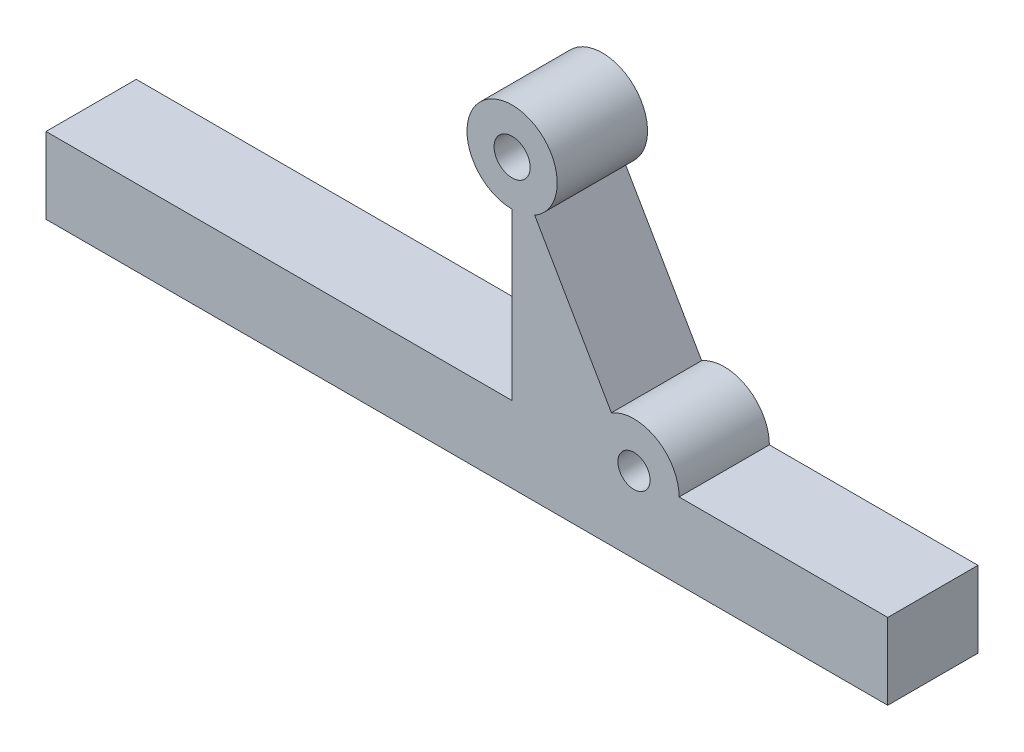
SolidWorks part; units mm, degrees
ref_plane "前视基准面" through (0, 0, 0) normal (0, 0, 1) x (1, 0, 0)
ref_plane "上视基准面" through (0, 0, 0) normal (0, 1, 0) x (1, 0, 0)
ref_plane "右视基准面" through (0, 0, 0) normal (1, 0, 0) x (0, 0, -1)
sketch "草图2" plane through (0, 0, 0) normal (0, 0, 1) x (1, 0, 0)
  line L1 (51.2871, 0) -> (-51.2871, 0) construction
  line L2 (10.9982, 4.3291) -> (2.5018, 19.0309)
  line L3 (0, -20.8591) -> (0, 20.8591) construction
  line L5 (-51.637, 0) -> (8.5, 0)
  line L6 (41.6122, 0) -> (41.6122, -8.4308)
  line L7 (41.6122, -8.4308) -> (-51.637, -8.4308)
  line L8 (-51.637, -8.4308) -> (-51.637, 0)
  line L9 (11.7192, 0) -> (15.2808, 0)
  line L10 (0, 18.36) -> (0, 0)
  line L11 (18.5, 0) -> (41.6122, 0)
  arc A0 (2.5018, 19.0309) -> (0, 18.36) centre (0, 23.36) ccw
  arc A1 (18.5, 0) -> (10.9982, 4.3291) centre (13.5, 0) ccw
  circle A2 centre (0, 23.36) radius 2
  circle A3 centre (13.5, 0) radius 1.7808
  point P16 (0, 0)
  point P22 (0, 0)
  point P23 (0, 0)
  point P24 (0, 0)
extrude "凸台-拉伸1" add sketch "草图2" along normal mid plane 10
